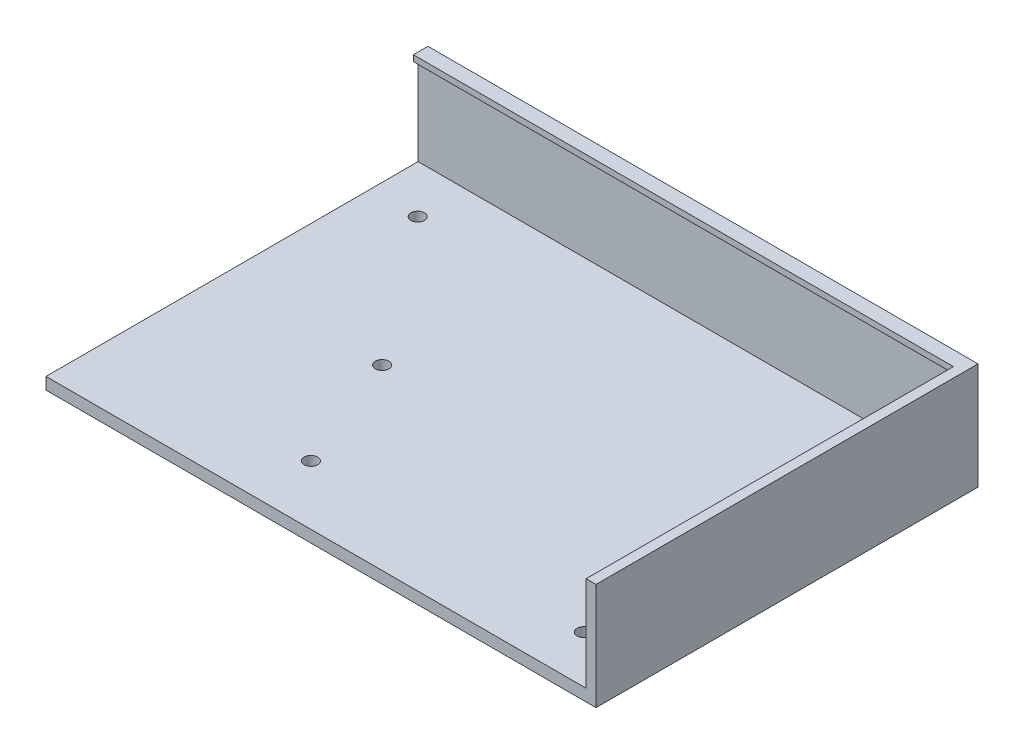
SolidWorks part; units mm, degrees
ref_plane "Front Plane" through (0, 0, 0) normal (0, 0, 1) x (1, 0, 0)
ref_plane "Top Plane" through (0, 0, 0) normal (0, 1, 0) x (1, 0, 0)
ref_plane "Right Plane" through (0, 0, 0) normal (1, 0, 0) x (0, 0, -1)
sketch "Sketch1" plane through (0, 0, 0) normal (0, 1, 0) x (1, 0, 0)
  line L1 (-139.1, -96.6) -> (139.1, -96.6)
  line L2 (-139.1, -96.6) -> (-139.1, 96.6)
  line L3 (-139.1, 96.6) -> (139.1, 96.6)
  line L4 (139.1, -96.6) -> (139.1, 96.6)
  line L5 (-139.1, -96.6) -> (139.1, 96.6) construction
  line L6 (-139.1, 96.6) -> (139.1, -96.6) construction
  dimension "D1" = 278.2
  dimension "D2" = 193.2
extrude "Shell Block" add sketch "Sketch1" along normal blind 27
ref_plane "Shell Front" through (0, 27, 0) normal (0, 1, 0) x (1, 0, 0)
sketch "Sketch2" plane through (0, 27, 0) normal (0, 1, 0) x (1, 0, 0)
  line L1 (-136.6, -92.9) -> (136.6, -92.9)
  line L2 (-136.6, -92.9) -> (-136.6, 92.9)
  line L3 (-136.6, 92.9) -> (136.6, 92.9)
  line L4 (136.6, -92.9) -> (136.6, 92.9)
  line L5 (-136.6, -92.9) -> (136.6, 92.9) construction
  line L6 (-136.6, 92.9) -> (136.6, -92.9) construction
  dimension "D1" = 273.2
  dimension "D2" = 185.8
extrude "Front Opening" cut sketch "Sketch2" against normal blind 1.5
ref_plane "Under Lip" through (0, 25.5, 0) normal (0, 1, 0) x (1, 0, 0)
sketch "Sketch3" plane through (0, 25.5, 0) normal (0, 1, 0) x (1, 0, 0)
  line L1 (-136.6, -94.1) -> (136.6, -94.1)
  line L2 (-136.6, -94.1) -> (-136.6, 94.1)
  line L3 (-136.6, 94.1) -> (136.6, 94.1)
  line L4 (136.6, -94.1) -> (136.6, 94.1)
  line L5 (-136.6, -94.1) -> (136.6, 94.1) construction
  line L6 (-136.6, 94.1) -> (136.6, -94.1) construction
  dimension "D1" = 273.2
  dimension "D2" = 188.2
extrude "Display Pocket" cut sketch "Sketch3" against normal blind 22.5
ref_plane "Back Inner" through (0, 3, 0) normal (0, 1, 0) x (1, 0, 0)
sketch "Sketch4" plane through (0, 3, 0) normal (0, 1, 0) x (1, 0, 0)
  line L1 (-69, 28) -> (-66, 28)
  line L2 (-69, 28) -> (-69, 84)
  line L3 (-69, 84) -> (-66, 84)
  line L4 (-66, 28) -> (-66, 84)
  line L6 (-69, -84) -> (-66, -84)
  line L7 (-69, -84) -> (-69, -28)
  line L8 (-69, -28) -> (-66, -28)
  line L9 (-66, -84) -> (-66, -28)
  line L11 (-77, 28) -> (-74, 28)
  line L12 (-77, 28) -> (-77, 84)
  line L13 (-77, 84) -> (-74, 84)
  line L14 (-74, 28) -> (-74, 84)
  line L16 (-77, -84) -> (-74, -84)
  line L17 (-77, -84) -> (-77, -28)
  line L18 (-77, -28) -> (-74, -28)
  line L19 (-74, -84) -> (-74, -28)
  line L21 (-85, 28) -> (-82, 28)
  line L22 (-85, 28) -> (-85, 84)
  line L23 (-85, 84) -> (-82, 84)
  line L24 (-82, 28) -> (-82, 84)
  line L26 (-85, -84) -> (-82, -84)
  line L27 (-85, -84) -> (-85, -28)
  line L28 (-85, -28) -> (-82, -28)
  line L29 (-82, -84) -> (-82, -28)
  line L31 (-93, 28) -> (-90, 28)
  line L32 (-93, 28) -> (-93, 84)
  line L33 (-93, 84) -> (-90, 84)
  line L34 (-90, 28) -> (-90, 84)
  line L36 (-93, -84) -> (-90, -84)
  line L37 (-93, -84) -> (-93, -28)
  line L38 (-93, -28) -> (-90, -28)
  line L39 (-90, -84) -> (-90, -28)
  line L41 (-101, 28) -> (-98, 28)
  line L42 (-101, 28) -> (-101, 84)
  line L43 (-101, 84) -> (-98, 84)
  line L44 (-98, 28) -> (-98, 84)
  line L46 (-101, -84) -> (-98, -84)
  line L47 (-101, -84) -> (-101, -28)
  line L48 (-101, -28) -> (-98, -28)
  line L49 (-98, -84) -> (-98, -28)
  line L51 (-109, 28) -> (-106, 28)
  line L52 (-109, 28) -> (-109, 84)
  line L53 (-109, 84) -> (-106, 84)
  line L54 (-106, 28) -> (-106, 84)
  line L56 (-109, -84) -> (-106, -84)
  line L57 (-109, -84) -> (-109, -28)
  line L58 (-109, -28) -> (-106, -28)
  line L59 (-106, -84) -> (-106, -28)
  line L61 (-117, 28) -> (-114, 28)
  line L62 (-117, 28) -> (-117, 84)
  line L63 (-117, 84) -> (-114, 84)
  line L64 (-114, 28) -> (-114, 84)
  line L66 (-117, -84) -> (-114, -84)
  line L67 (-117, -84) -> (-117, -28)
  line L68 (-117, -28) -> (-114, -28)
  line L69 (-114, -84) -> (-114, -28)
  line L71 (-125, 28) -> (-122, 28)
  line L72 (-125, 28) -> (-125, 84)
  line L73 (-125, 84) -> (-122, 84)
  line L74 (-122, 28) -> (-122, 84)
  line L76 (-125, -84) -> (-122, -84)
  line L77 (-125, -84) -> (-125, -28)
  line L78 (-125, -28) -> (-122, -28)
  line L79 (-122, -84) -> (-122, -28)
extrude "Vent Slots" cut sketch "Sketch4" against normal blind 4
sketch "Sketch5" plane through (0, 0, 0) normal (1, 0, 0) x (0, 0, -1)
  line L1 (-29, 5) -> (29, 5)
  line L2 (-29, 5) -> (-29, 21)
  line L3 (-29, 21) -> (29, 21)
  line L4 (29, 5) -> (29, 21)
extrude "Cable Exit (-X short side)" cut sketch "Sketch5" against normal blind 140.1
sketch "Sketch6" plane through (0, 3, 0) normal (0, 1, 0) x (1, 0, 0)
  circle A0 centre (-40, -45) radius 1.7
  circle A1 centre (-40, 45) radius 1.7
  circle A2 centre (40, -45) radius 1.7
  circle A3 centre (40, 45) radius 1.7
  circle A4 centre (-52, -15) radius 1.7
  circle A5 centre (-52, 15) radius 1.7
  circle A6 centre (52, -15) radius 1.7
  circle A7 centre (52, 15) radius 1.7
  circle A8 centre (-12, -82) radius 1.7
  circle A9 centre (-12, 82) radius 1.7
  circle A10 centre (12, -82) radius 1.7
  circle A11 centre (12, 82) radius 1.7
  circle A12 centre (-124, -12) radius 1.7
  circle A13 centre (-124, 12) radius 1.7
  circle A14 centre (124, -12) radius 1.7
  circle A15 centre (124, 12) radius 1.7
extrude "Bolt Holes" cut sketch "Sketch6" against normal blind 4
sketch "Sketch7" plane through (0, 0, 0) normal (0, 1, 0) x (1, 0, 0)
  line L1 (-200, -200) -> (0, -200)
  line L2 (-200, -200) -> (-200, 200)
  line L3 (-200, 200) -> (0, 200)
  line L4 (0, -200) -> (0, 200)
extrude "Keep one half (X)" cut sketch "Sketch7" against normal through all and the other way through all
sketch "Sketch8" plane through (0, 0, 0) normal (0, 1, 0) x (1, 0, 0)
  line L1 (-200, 0) -> (200, 0)
  line L2 (-200, 0) -> (-200, -200)
  line L3 (-200, -200) -> (200, -200)
  line L4 (200, 0) -> (200, -200)
extrude "Keep one quarter (Z)" cut sketch "Sketch8" against normal through all and the other way through all
equation "\"DispL\"= 272.0"
equation "\"DispW\"= 187.0"
equation "\"DispT\"= 20.0"
equation "\"Clr\"= 0.6"
equation "\"Wall\"= 2.5"
equation "\"BackT\"= 3.0"
equation "\"CableRoom\"= 4.0"
equation "\"LipW\"= 1.2"
equation "\"LipT\"= 1.5"
equation "\"CableW\"= 58.0"
equation "\"CableH\"= 16.0"
equation "\"BoltD\"= 3.4"
equation "\"ShellL\"= \"DispL\" + 2 * \"Clr\" + 2 * \"Wall\""
equation "\"ShellW\"= \"DispW\" + 2 * \"Clr\" + 2 * \"Wall\""
equation "\"ShellH\"= \"BackT\" + \"DispT\" + \"CableRoom\""
equation "\"D1@Sketch1\" = \"ShellL\""
equation "\"D2@Sketch1\" = \"ShellW\""
equation "\"D1@Shell Block\" = \"ShellH\""
equation "\"D1@Shell Front\" = \"ShellH\""
equation "\"D1@Sketch2\" = \"DispL\" + 2 * \"Clr\""
equation "\"D2@Sketch2\" = \"DispW\" + 2 * \"Clr\" - 2 * \"LipW\""
equation "\"D1@Front Opening\" = \"LipT\""
equation "\"D1@Under Lip\" = \"ShellH\" - \"LipT\""
equation "\"D1@Sketch3\" = \"DispL\" + 2 * \"Clr\""
equation "\"D2@Sketch3\" = \"DispW\" + 2 * \"Clr\""
equation "\"D1@Display Pocket\" = \"ShellH\" - \"LipT\" - \"BackT\""
equation "\"D1@Back Inner\" = \"BackT\""
